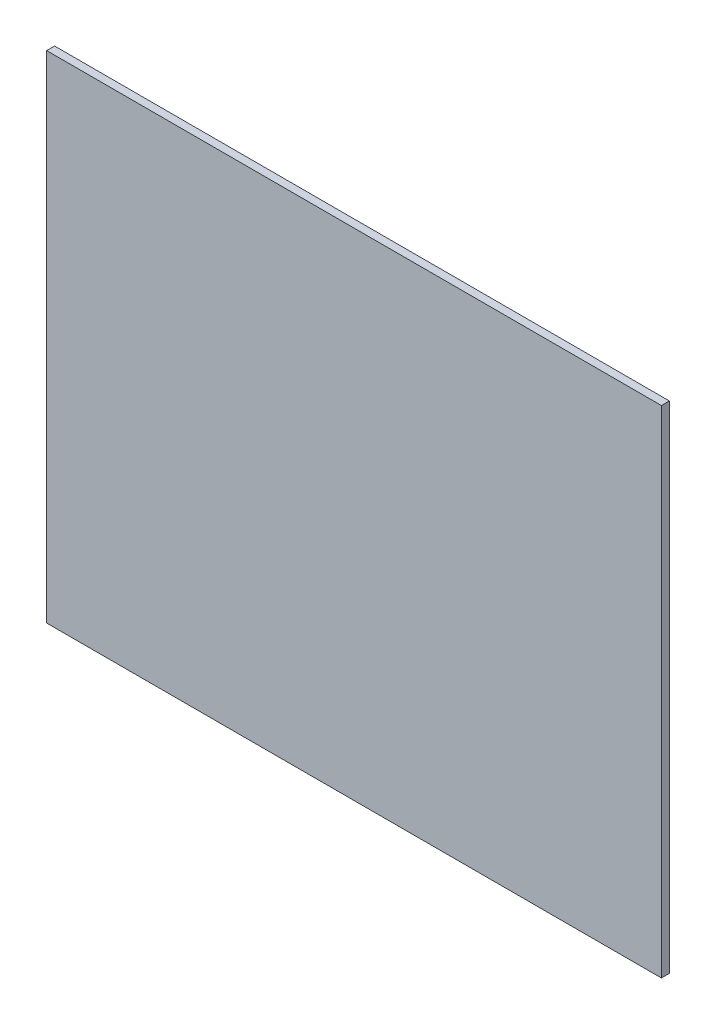
SolidWorks part; units mm, degrees
material "6061 Alloy"
ref_plane "Front Plane" through (0, 0, 0) normal (0, 0, 1) x (1, 0, 0)
ref_plane "Top Plane" through (0, 0, 0) normal (0, 1, 0) x (1, 0, 0)
ref_plane "Right Plane" through (0, 0, 0) normal (1, 0, 0) x (0, 0, -1)
sketch "Sketch1" plane through (0, 0, 0) normal (0, 0, 1) x (1, 0, 0)
  line L1 (-77.5, -62.5) -> (77.5, -62.5)
  line L2 (-77.5, -62.5) -> (-77.5, 62.5)
  line L3 (-77.5, 62.5) -> (77.5, 62.5)
  line L4 (77.5, -62.5) -> (77.5, 62.5)
  line L5 (-77.5, -62.5) -> (77.5, 62.5) construction
  line L6 (-77.5, 62.5) -> (77.5, -62.5) construction
  point P0 (0, 0)
  dimension "D1" = 125
  dimension "D2" = 155
extrude "Boss-Extrude1" add sketch "Sketch1" along normal blind 2
